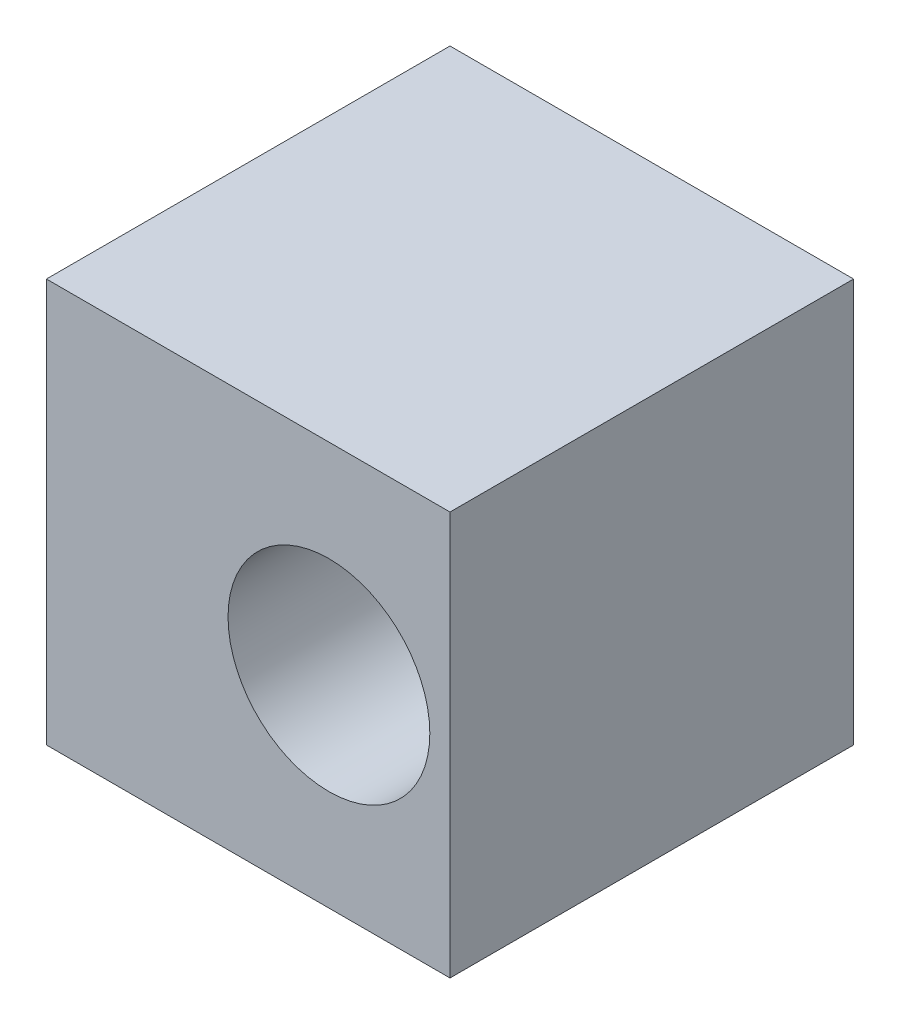
SolidWorks part; units mm, degrees
ref_plane "Front Plane" through (0, 0, 0) normal (0, 0, 1) x (1, 0, 0)
ref_plane "Top Plane" through (0, 0, 0) normal (0, 1, 0) x (1, 0, 0)
ref_plane "Right Plane" through (0, 0, 0) normal (1, 0, 0) x (0, 0, -1)
sketch "Sketch1" plane through (0, 0, 0) normal (0, 0, 1) x (1, 0, 0)
  line L1 (0, 0) -> (10, 0)
  line L2 (0, 0) -> (0, 10)
  line L3 (0, 10) -> (10, 10)
  line L4 (10, 0) -> (10, 10)
extrude "Boss-Extrude1" add sketch "Sketch1" along normal blind 10
sketch "Sketch2" plane through (0, 0, 0) normal (0, 0, 1) x (1, 0, 0)
  circle A0 centre (7, 5) radius 2.5
extrude "Cut-Extrude1" cut sketch "Sketch2" along normal through all
